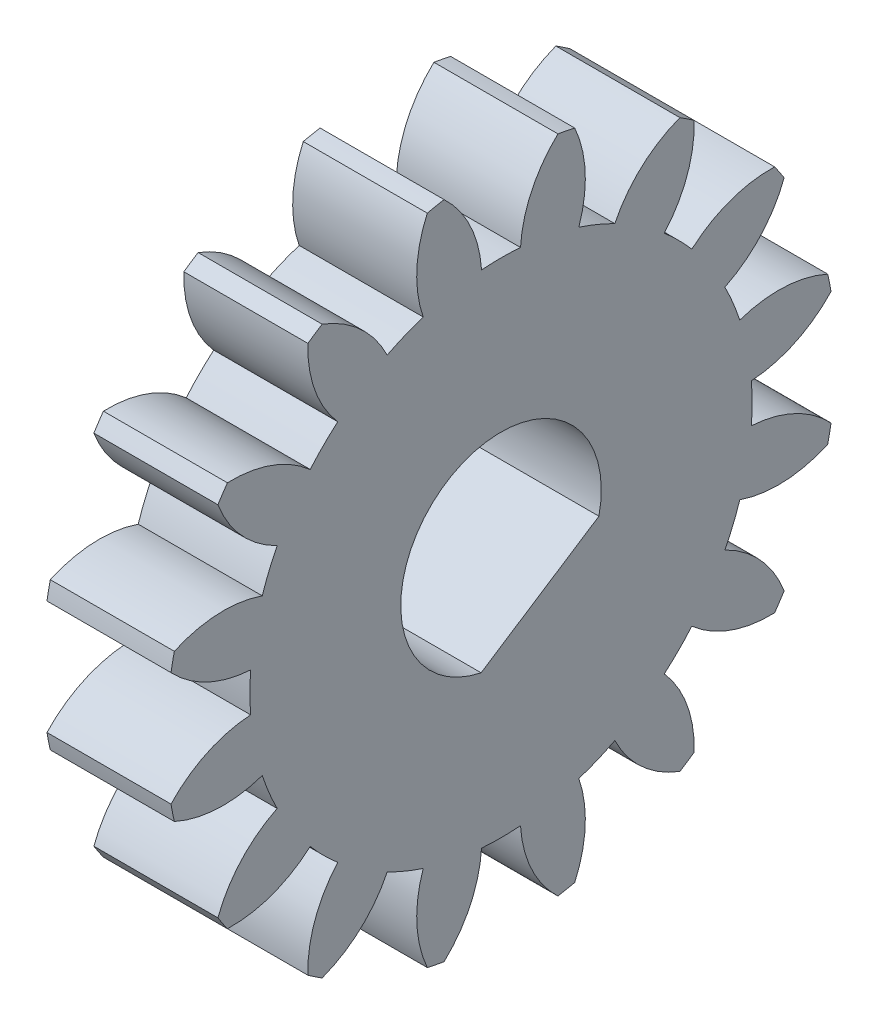
SolidWorks part; units mm, degrees
ref_plane "Plane1" through (0, 0, 0) normal (0, 0, 1) x (1, 0, 0)
ref_plane "Plane2" through (0, 0, 0) normal (0, 1, 0) x (1, 0, 0)
ref_plane "Plane3" through (0, 0, 0) normal (1, 0, 0) x (0, 0, -1)
sketch "HoldingSke" plane through (0, 0, 0) normal (0, 1, 0) x (1, 0, 0)
  line L0 (0, 0) -> (1.0681, -0.3063)
  line L1 (-15, 0) -> (100, 0) construction
  line L2 (0, 0) -> (-2.1039, 2.3779)
  line L3 (0, 0) -> (-11.863, 4.5341)
  line L4 (0, 0) -> (8.3015, 2.3804)
  line L5 (0, 0) -> (-46.8476, -17.4728)
  line L6 (0, 0) -> (-1.6579, -1.1186)
  line L7 (-2.1039, 2.3779) -> (8.6586, 51.2059)
  line L8 (-76.2, 54.61) -> (-76.1, 54.61)
  line L9 (-71.009, 38.7566) -> (-53.1078, 45.2721)
  line L10 (-76.2, 71.12) -> (104.1128, 71.12)
  line L11 (0, 0) -> (-2, 0)
  line L12 (-76.2, 101.6) -> (-76.166, 101.6)
  line L13 (24.9733, 27.94) -> (52.9518, 28.4284)
  line L14 (24.9733, 27.94) -> (24.9743, 27.94)
  line L15 (24.9733, 27.94) -> (100.4006, 29.5858)
  line L16 (-63.627, -0.9) -> (-12.827, -0.9)
  circle A0 centre (0, 0) radius 0.5
  circle A1 centre (0, 0) radius 6.074
  circle A2 centre (0, 0) radius 37.5
  circle A3 centre (0, 0) radius 0.5
  dimension "MHD" = 12.148
  dimension "Hub_dia" = 75
  dimension "Bore" = 1
  dimension "MBD" = 1
  dimension "Num_teeth" = 16
  dimension "Pitch" = 1.1111
  dimension "Overall_len" = 50
  dimension "Show_teeth" = 16
  dimension "Thickness" = 2
  dimension "OAL" = 50.0001
  dimension "T_dim" = 0.1
  dimension "Ap" = 20
  dimension "H" = 19.05
  dimension "Pitch_radius" = 180.3128
  dimension "Width" = 2
  dimension "Backlash" = 0.034
  dimension "Addendum_fac" = 1
  dimension "Dedendum_fac" = 1.25
  dimension "Clearance_fac" = 0.25
  dimension "Dedendum_add" = 0.001
  dimension "Module" = 0.9
sketch "BasProSke" plane through (0, 0, 0) normal (0, 1, 0) x (1, 0, 0)
  line L0 (-10, 0) -> (60, 0) construction
  line L1 (0, 0) -> (0, 8.1)
  line L2 (0, 0) -> (2, 0)
  line L3 (2, 0) -> (2, 8.1)
  line L4 (2, 8.1) -> (0, 8.1)
  dimension "Thickness" = 2
  dimension "Diameter" = 16.2
revolve "Base-Revolve" add sketch "BasProSke" angle 360 about L0
sketch "TooCutSke" plane through (0, 0, 0) normal (1, 0, 0) x (0, 0, -1)
  line L1 (0, 0) -> (0, 107) construction
  line L2 (0, 0) -> (-0.7652, 7.1592) construction
  line L3 (0, 0) -> (-2.798, 14.0663) construction
  line L4 (-0.7652, 7.1592) -> (-1.399, 7.0332) construction
  arc A0 (0.4711, 6.0557) -> (-0.4711, 6.0557) centre (0, 0) ccw
  arc A1 (1.4, 8.0039) -> (-1.4, 8.0039) centre (0, 0) ccw
  circle A2 centre (0, 0) radius 7.2 construction
  circle A3 centre (0, 0) radius 6.7658 construction
  arc A4 (-0.4711, 6.0557) -> (-1.4, 8.0039) centre (-3.3458, 5.8806) ccw
  arc A5 (1.4, 8.0039) -> (0.4711, 6.0557) centre (3.3458, 5.8806) ccw
  dimension "Root_dia" = 12.148
  dimension "Overcut_dia" = 16.2508
  dimension "Pitch_dia" = 14.4
  dimension "Base_dia" = 13.5316
  dimension "Flank_rad" = 2.88
  dimension "Half_ang" = 11.25
  dimension "Half_CT" = 0.6462
extrude "ToothCut" cut sketch "TooCutSke" along normal through all
fillet "Breaks" [suppressed] radius 0.018
fillet "RootFillets" [suppressed] radius 0.226
pattern_circular "TeethCuts" count 16 every 22.5 about axis through (-10, 0, 0) along (1, 0, 0) of "ToothCut", "RootFillets", "Breaks"
sketch "HubNeaOneSke" plane through (0, 0, 0) normal (-1, 0, 0) x (0, 0, 1)
  circle A0 centre (0, 0) radius 6.074
  dimension "Diameter" = 12.148
extrude "HubNearOne" [suppressed] add sketch "HubNeaOneSke" along normal blind 48.0001
sketch "HubNeaBotSke" plane through (0, 0, 0) normal (-1, 0, 0) x (0, 0, 1)
  circle A0 centre (0, 0) radius 6.074
  dimension "Diameter" = 12.148
extrude "HubNearBoth" [suppressed] add sketch "HubNeaBotSke" along normal blind 24
ref_plane "FarPln" through (2, 0, 0) normal (1, 0, 0) x (0, 0, -1)
sketch "HubFarSke" plane through (2, 0, 0) normal (1, 0, 0) x (0, 0, -1)
  circle A0 centre (0, 0) radius 6.074
  dimension "Diameter" = 12.148
extrude "HubFar" [suppressed] add sketch "HubFarSke" along normal blind 24
sketch "BorSke" plane through (0, 0, 0) normal (1, 0, 0) x (0, 0, -1)
  line L0 (2.3681, -0.5222) -> (-0.4816, -2.3767)
  arc A0 (2.3681, -0.5222) -> (-0.4816, -2.3767) centre (0, 0) ccw
  dimension "D1" = 2.425
  dimension "D2" = 3.4
extrude "Bore" cut sketch "BorSke" along normal mid plane 100.0001
sketch "KeySke" plane through (0, 0, 0) normal (1, 0, 0) x (0, 0, -1)
  line L0 (-0.05, 0) -> (-0.05, 0.6)
  line L1 (-0.05, 0.6) -> (0.05, 0.6)
  line L2 (0.05, 0.6) -> (0.05, 0)
  line L3 (0, 0) -> (0, 34) construction
  line L4 (-0.05, 0) -> (0.05, 0)
  dimension "Offset" = 0.6
  dimension "Width" = 0.1
extrude "Keyway" [suppressed] cut sketch "KeySke" along normal mid plane 100.0001
pattern_circular "Keyway2" [suppressed] count 2 every 90 about axis through (-10, 0, 0) along (1, 0, 0)
scale "Scale1" scale about centroid uniform scaling no x scale factor 1.5 y scale factor 1 z scale factor 1
equation "' \"Module@HoldingSke\" = 6.35"
equation "' \"Num_teeth@HoldingSke\" = 12"
equation "' \"Ap@HoldingSke\" =  20"
equation "' \"Ap@HoldingSke\" = 20"
equation "' \"Width@HoldingSke\" = 0.5 * 25.4"
equation "' \"Hub_dia@HoldingSke\"= 1 * 25.4"
equation "' \"Hub_dia@HoldingSke\" = 1 * 25.4"
equation "' \"Overall_len@HoldingSke\" = 1.0 * 25.4"
equation "' \"Bore@HoldingSke\" = 0.75 * 25.4"
equation "' \"T_dim@HoldingSke\" = 0.1 * 25.4"
equation "' \"Width@KeySke\" = 0.25 * 25.4"
equation "' \"Show_teeth@HoldingSke\" = 13"
equation "' \"Backlash@HoldingSke\" = 0.009 * 25.4"
equation "' \"Addendum_fac@HoldingSke\" = 1.0"
equation "' \"Dedendum_fac@HoldingSke\" = 1.25"
equation "' \"Dedendum_add@HoldingSke\" = 0.00005 * 25.4"
equation "' \"Clearance_fac@HoldingSke\" = 0.25"
equation "\"Pitch@HoldingSke\" = 1 / \"Module@HoldingSke\""
equation "\"Overcut_dia@TooCutSke\" = (\"Num_teeth@HoldingSke\" + 2 * \"Addendum_fac@HoldingSke\") / \"Pitch@HoldingSke\" + 0.002 * 25.4"
equation "\"Pitch_dia@TooCutSke\" = \"Num_teeth@HoldingSke\" / \"Pitch@HoldingSke\""
equation "\"Base_dia@TooCutSke\" = \"Num_teeth@HoldingSke\" / \"Pitch@HoldingSke\" * cos((\"Ap@HoldingSke\"  * 3.14159265 / 180))"
equation "\"Root_dia@TooCutSke\" = (\"Num_teeth@HoldingSke\" + 2) / \"Pitch@HoldingSke\" - 2 * (\"Addendum_fac@HoldingSke\" + \"Dedendum_fac@HoldingSke\") / \"Pitch@HoldingSke\" - \"Dedendum_add@HoldingSke\" * 2"
equation "\"Half_ang@TooCutSke\" = 180 / \"Num_teeth@HoldingSke\""
equation "\"Half_CT@TooCutSke\" = \"Num_teeth@HoldingSke\" / \"Pitch@HoldingSke\" * sin((3.14159265 / 2 / \"Num_teeth@HoldingSke\")) / 2 - 7 * \"Backlash@HoldingSke\" / 4"
equation "\"Flank_rad@TooCutSke\" = \"Num_teeth@HoldingSke\" / \"Pitch@HoldingSke\" / 5"
equation "\"Radius@RootFillets\" = \"Clearance_fac@HoldingSke\" / \"Pitch@HoldingSke\" + \"Dedendum_add@HoldingSke\""
equation "\"Break_rad@Breaks\" = 0.02 / \"Pitch@HoldingSke\""
equation "\"Thickness@HoldingSke\" = \"Width@HoldingSke\""
equation "\"OAL@HoldingSke\" = \"Thickness@HoldingSke\""
equation "\"MHD@HoldingSke\" = (\"Num_teeth@HoldingSke\" + 2) / \"Pitch@HoldingSke\" - 2 * (\"Addendum_fac@HoldingSke\" + \"Dedendum_fac@HoldingSke\")  / \"Pitch@HoldingSke\" - \"Dedendum_add@HoldingSke\" * 2"
equation "\"MBD@HoldingSke\" = (\"Num_teeth@HoldingSke\" + 2) / \"Pitch@HoldingSke\" - 2 * (\"Addendum_fac@HoldingSke\" + \"Dedendum_fac@HoldingSke\")  / \"Pitch@HoldingSke\" - \"Dedendum_add@HoldingSke\" * 2 - 0.002 * 25.4"
equation "\"MHD@HoldingSke\" = ((sgn( \"MHD@HoldingSke\" - \"Hub_dia@HoldingSke\" )-1)*( \"MHD@HoldingSke\" - \"Hub_dia@HoldingSke\" ))/-2+ \"Hub_dia@HoldingSke\""
equation "\"MBD@HoldingSke\" = ((sgn( \"MBD@HoldingSke\" - \"Bore@HoldingSke\" )-1)*( \"MBD@HoldingSke\" - \"Bore@HoldingSke\" ))/-2+ \"Bore@HoldingSke\""
equation "\"OAL@HoldingSke\" = ((sgn( \"OAL@HoldingSke\" - \"Overall_len@HoldingSke\" )+1)*( \"OAL@HoldingSke\" - \"Overall_len@HoldingSke\" ))/2 + \"Overall_len@HoldingSke\" + 0.000002 * 25.4"
equation "\"Num_teeth@TeethCuts\" = int( \"Show_teeth@HoldingSke\" ) + 1"
equation "\"Num_teeth@TeethCuts\" = ((sgn( \"Num_teeth@TeethCuts\" - \"Num_teeth@HoldingSke\" )-1)*( \"Num_teeth@TeethCuts\" - \"Num_teeth@HoldingSke\" ))/-2+ \"Num_teeth@HoldingSke\""
equation "\"Num_teeth@TeethCuts\" = ((sgn( \"Num_teeth@TeethCuts\" - 2.0)+1)*( \"Num_teeth@TeethCuts\" - 2.0))/2 +2.0"
equation "\"Angle@TeethCuts\" = 360.0 / \"Num_teeth@HoldingSke\""
equation "\"Diameter@BasProSke\" = (\"Num_teeth@HoldingSke\" + 2 * \"Addendum_fac@HoldingSke\") / \"Pitch@HoldingSke\""
equation "\"Thickness@BasProSke\"  = \"Thickness@HoldingSke\""
equation "' \"Fillet_rad@BasProSke\" =  \"Thickness@HoldingSke\" * 0.05"
equation "' \"Fillet_rad@BasProSke\" = \"Thickness@HoldingSke\" * 0.05"
equation "\"MHD@HoldingSke\" = ((sgn( \"MHD@HoldingSke\" - \"Root_dia@TooCutSke\" )-1)*( \"MHD@HoldingSke\" - \"Root_dia@TooCutSke\" ))/-2+ \"Root_dia@TooCutSke\""
equation "\"Diameter@HubNeaOneSke\" = \"MHD@HoldingSke\""
equation "\"Length@HubNearOne\" = \"OAL@HoldingSke\" - \"Thickness@BasProSke\""
equation "\"Diameter@HubNeaBotSke\" = \"MHD@HoldingSke\""
equation "\"Length@HubNearBoth\" = ( \"OAL@HoldingSke\" - \"Thickness@BasProSke\" ) / 2.0"
equation "\"Thickness@FarPln\" = \"Thickness@BasProSke\""
equation "\"Diameter@HubFarSke\" = \"MHD@HoldingSke\""
equation "\"Length@HubFar\" = ( \"OAL@HoldingSke\" - \"Thickness@BasProSke\" ) / 2.0"
equation "\"D1@Bore\" = \"OAL@HoldingSke\" * 2.0"
equation "\"D1@Keyway\" = \"OAL@HoldingSke\" * 2.0"
equation "\"Offset@KeySke\" = \"T_dim@HoldingSke\" + \"MBD@HoldingSke\" / 2.0"
